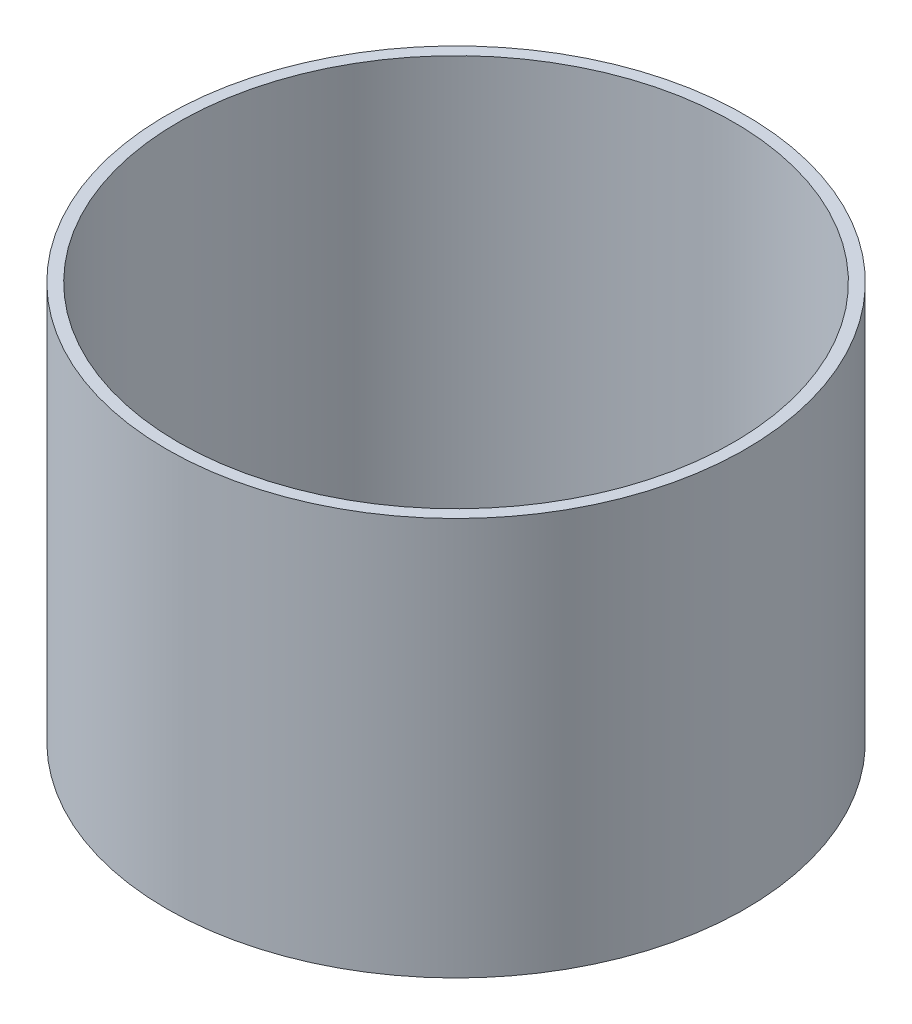
SolidWorks part; units mm, degrees
material "PVC Rígido"
ref_plane "Alzado" through (0, 0, 0) normal (0, 0, 1) x (1, 0, 0)
ref_plane "Planta" through (0, 0, 0) normal (0, 1, 0) x (1, 0, 0)
ref_plane "Vista lateral" through (0, 0, 0) normal (1, 0, 0) x (0, 0, -1)
sketch "Croquis2" plane through (0, 0, 0) normal (0, 1, 0) x (1, 0, 0)
  circle A0 centre (0, 0) radius 76.7
  circle A1 centre (0, 0) radius 80
  dimension "D1" = 160
  dimension "D2" = 3.3
extrude "Saliente-Extruir1" add sketch "Croquis2" against normal blind 110
